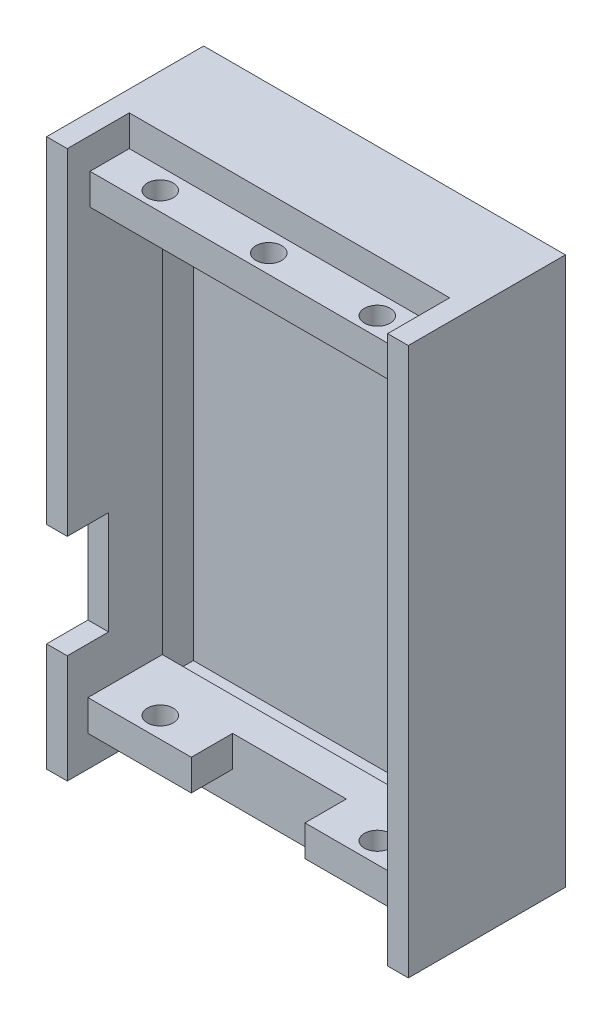
SolidWorks part; units mm, degrees
ref_plane "前视基准面" through (0, 0, 0) normal (0, 0, 1) x (1, 0, 0)
ref_plane "上视基准面" through (0, 0, 0) normal (0, 1, 0) x (1, 0, 0)
ref_plane "右视基准面" through (0, 0, 0) normal (1, 0, 0) x (0, 0, -1)
sketch "草图1" plane through (0, 0, 0) normal (0, 0, 1) x (1, 0, 0)
  line L1 (-15, 20) -> (20, 20)
  line L2 (-15, 20) -> (-15, -33)
  line L3 (-15, -33) -> (20, -33)
  line L4 (20, 20) -> (20, -33)
  dimension "D1" = 53
  dimension "D2" = 35
  dimension "D3" = 15
  dimension "D4" = 20
extrude "凸台-拉伸1" add sketch "草图1" along normal blind 2
sketch "草图2" plane through (0, 0, 2) normal (0, 0, 1) x (1, 0, 0)
  line L0 (-15, 20) -> (-15, -33)
  line L1 (-15, -33) -> (-13, -33)
  line L2 (-15, -33) -> (20, -33) construction
  line L3 (-13, -33) -> (-13, 20)
  line L4 (20, 20) -> (-15, 20) construction
  line L5 (-13, 20) -> (-15, 20)
  line L6 (20, 20) -> (20, -33)
  line L7 (20, -33) -> (18, -33)
  line L8 (18, -33) -> (18, 20)
  line L9 (18, 20) -> (20, 20)
  dimension "D1" = 2
  dimension "D2" = 2
extrude "凸台-拉伸2" add sketch "草图2" along normal blind 13.2
sketch "草图3" plane through (0, 0, 2) normal (0, 0, 1) x (1, 0, 0)
  line L0 (-13, 20) -> (-13, 17)
  line L1 (-13, -33) -> (-13, 20) construction
  line L2 (-13, 17) -> (18, 17)
  line L3 (18, 20) -> (18, -33) construction
  line L4 (18, 17) -> (18, 20)
  line L5 (18, 20) -> (-13, 20)
  line L6 (18, -33) -> (-13, -33)
  line L7 (-13, -33) -> (-13, -30)
  line L8 (-13, -30) -> (18, -30)
  line L9 (18, -30) -> (18, -33)
  dimension "D1" = 3
  dimension "D2" = 3
extrude "凸台-拉伸3" add sketch "草图3" along normal blind 7.2
sketch "草图4" plane through (0, 0, 2) normal (0, 0, 1) x (1, 0, 0)
  line L0 (-13, 17) -> (-13, 14)
  line L1 (-13, -30) -> (-13, 17) construction
  line L2 (-13, 14) -> (18, 14)
  line L3 (18, 17) -> (18, -30) construction
  line L4 (18, 14) -> (18, 17)
  line L5 (18, 17) -> (-13, 17)
  line L6 (-13, -30) -> (18, -30)
  line L7 (18, -30) -> (18, -27)
  line L8 (18, -27) -> (-13, -27)
  line L9 (-13, -27) -> (-13, -30)
  dimension "D1" = 3
  dimension "D2" = 3
extrude "凸台-拉伸4" add sketch "草图4" along normal up to surface (13.2 mm away) up to face at (-14, -6.5, 15.2)
sketch "草图5" plane through (0, 17, 0) normal (0, 1, 0) x (1, 0, 0)
  line L0 (-13, -9.2) -> (18, -9.2) construction
  line L1 (-13, -15.2) -> (-13, -9.2) construction
  line L2 (18, -15.2) -> (18, -9.2) construction
  circle A0 centre (-8, -11.2) radius 1.25
  circle A1 centre (2.5, -11.2) radius 1.25
  circle A2 centre (13, -11.2) radius 1.25
  dimension "D2" = 2.5
  dimension "D3" = 2.5
  dimension "D6" = 2.5
  dimension "D1" = 2
  dimension "D4" = 2
  dimension "D5" = 2
  dimension "D7" = 5
  dimension "D8" = 5
  dimension "D9" = 10.5
extrude "切除-拉伸1" cut sketch "草图5" against normal up to next
sketch "草图7" plane through (0, 0, 15.2) normal (0, 0, 1) x (1, 0, 0)
  line L0 (-13, 17) -> (-13, 14)
  line L1 (-13, 14) -> (18, 14)
  line L2 (18, 14) -> (18, 17)
  line L3 (18, 17) -> (-13, 17)
extrude "切除-拉伸2" cut sketch "草图7" against normal blind 2.2
sketch "草图8" plane through (0, 0, 15.2) normal (0, 0, 1) x (1, 0, 0)
  line L0 (-13, -27) -> (-13, -30)
  line L1 (-13, -30) -> (18, -30)
  line L2 (18, -30) -> (18, -27)
  line L3 (18, -27) -> (-13, -27)
extrude "切除-拉伸3" cut sketch "草图8" against normal blind 2
sketch "草图9" plane through (0, -30, 0) normal (0, -1, 0) x (1, 0, 0)
  line L0 (18, 9.2) -> (-13, 9.2) construction
  line L1 (-13, 13.2) -> (-13, 9.2) construction
  line L2 (18, 13.2) -> (18, 9.2) construction
  circle A0 centre (-8, 11.2) radius 1.25
  circle A1 centre (13, 11.2) radius 1.25
  dimension "D3" = 2.5
  dimension "D4" = 2.5
  dimension "D1" = 2
  dimension "D2" = 2
  dimension "D5" = 5
  dimension "D6" = 5
sketch "草图10" plane through (0, 0, 13.2) normal (0, 0, 1) x (1, 0, 0)
  line L0 (-3, -27) -> (-3, -30)
  line L1 (18, -27) -> (-13, -27) construction
  line L2 (-13, -30) -> (18, -30) construction
  line L3 (-3, -30) -> (8, -30)
  line L4 (18, -30) -> (-13, -30) construction
  line L5 (8, -30) -> (8, -27)
  line L6 (18, -27) -> (-13, -27) construction
  line L7 (8, -27) -> (-3, -27)
  line L8 (-13, -27) -> (-13, -30) construction
  line L9 (18, -30) -> (18, -27) construction
  dimension "D1" = 10
  dimension "D2" = 10
extrude "切除-拉伸4" cut sketch "草图10" against normal up to surface (4 mm away) up to face at (2.5, -31.5, 9.2)
extrude "切除-拉伸5" cut sketch "草图9" against normal up to surface (3 mm away) contours A0 | A1 up to face at (2.5, -27, 9.4)
sketch "草图12" plane through (0, 0, 15.2) normal (0, 0, 1) x (1, 0, 0)
  line L0 (-15, -22.5) -> (-13, -22.5)
  line L1 (-15, 20) -> (-15, -33) construction
  line L2 (-13, -27) -> (-13, 14) construction
  line L3 (-13, -22.5) -> (-13, -12.5)
  line L4 (-13, -12.5) -> (-15, -12.5)
  line L5 (-15, -12.5) -> (-15, -22.5)
  line L6 (-15, -33) -> (-13, -33) construction
  dimension "D1" = 10.5
  dimension "D2" = 10
extrude "切除-拉伸6" cut sketch "草图12" against normal blind 4
sketch "草图13" plane through (0, 0, 2) normal (0, 0, 1) x (1, 0, 0)
  line L0 (-13, -27) -> (-13, 14) construction
  line L1 (-14, 17) -> (19, 17)
  line L2 (-14, 17) -> (-14, -30)
  line L3 (-14, -30) -> (19, -30)
  line L4 (19, 17) -> (19, -30)
  line L5 (-13, 14) -> (18, 14) construction
  dimension "D1" = 33
  dimension "D2" = 47
  dimension "D3" = 1
  dimension "D4" = 3
extrude "切除-拉伸7" cut sketch "草图13" along normal blind 4
